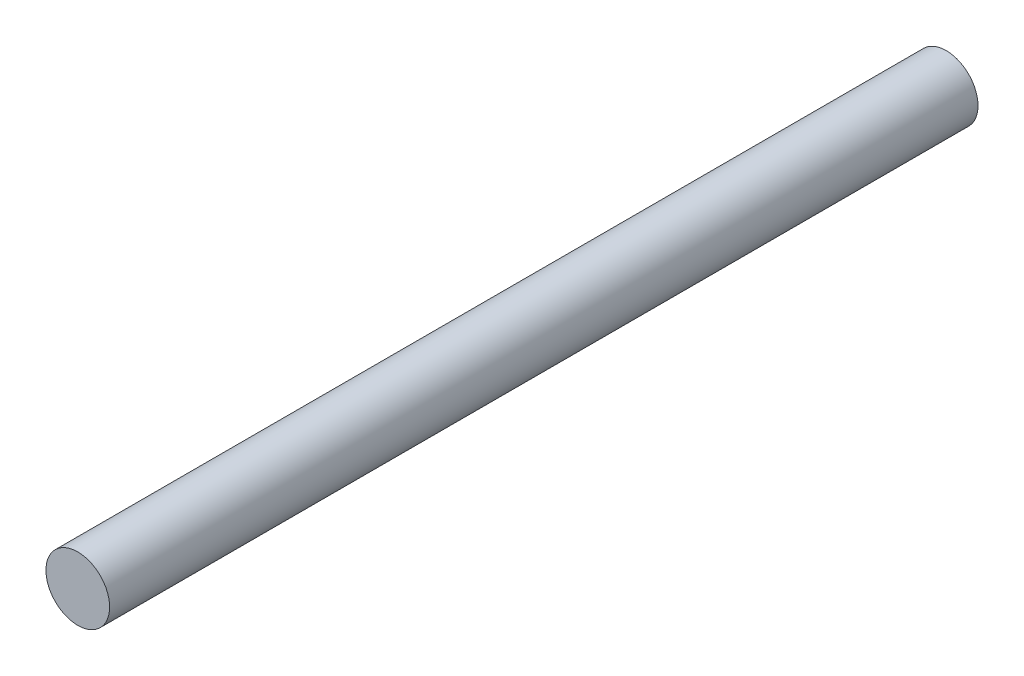
SolidWorks part; units mm, degrees
material "ABS"
ref_plane "Front Plane" through (0, 0, 0) normal (0, 0, 1) x (1, 0, 0)
ref_plane "Top Plane" through (0, 0, 0) normal (0, 1, 0) x (1, 0, 0)
ref_plane "Right Plane" through (0, 0, 0) normal (1, 0, 0) x (0, 0, -1)
other "Center of Mass"
sketch "Sketch1" plane through (0, 0, 0) normal (0, 0, 1) x (1, 0, 0)
  arc A2 (-12.65, 0) -> (0, 12.65) centre (0, 0) ccw
  circle A3 centre (0, 0) radius 12.65
  dimension "D1" = 0.1
extrude "Boss-Extrude1" add sketch "Sketch1" against normal blind 345
